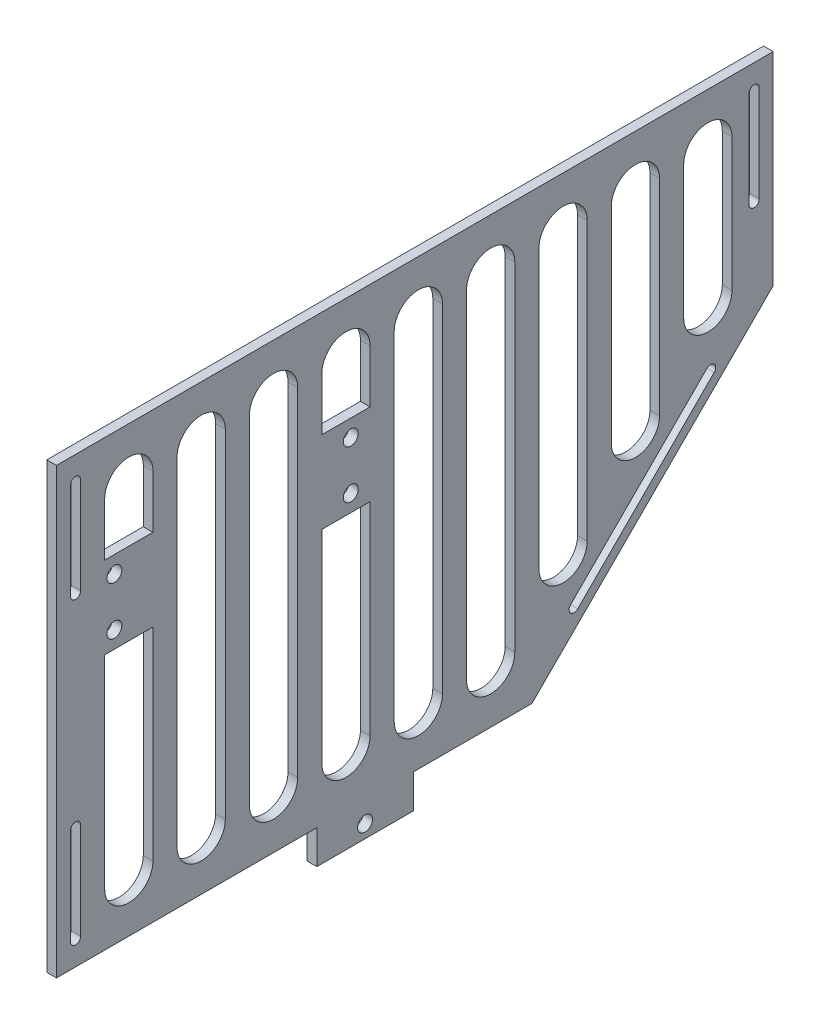
SolidWorks part; units mm, degrees
material "A-玻璃纤维"
ref_plane "前视基准面" through (0, 0, 0) normal (0, 0, 1) x (1, 0, 0)
ref_plane "上视基准面" through (0, 0, 0) normal (0, 1, 0) x (1, 0, 0)
ref_plane "右视基准面" through (0, 0, 0) normal (1, 0, 0) x (0, 0, -1)
sketch "草图2" plane through (0, 0, 0) normal (1, 0, 0) x (0, 0, -1)
  line L1 (-74.275, 46) -> (74.275, 46)
  line L2 (-74.275, 46) -> (-74.275, -46)
  line L3 (-74.275, -46) -> (74.275, -46)
  line L4 (74.275, 46) -> (74.275, -46)
  line L5 (0, -46) -> (0, 46) construction
  line L6 (-74.275, 0) -> (74.275, 0) construction
  point P0 (0, 0)
  dimension "D1" = 148.55
  dimension "D2" = 92
extrude "凸台-拉伸1" add sketch "草图2" along normal blind 2
sketch "草图3" plane through (2, 0, 0) normal (1, 0, 0) x (0, 0, -1)
  line L0 (24.275, -46) -> (74.275, 4)
  line L1 (-74.275, -46) -> (74.275, -46) construction
  line L2 (74.275, -46) -> (74.275, 46) construction
  dimension "D1" = 50
  dimension "D2" = 50
extrude "切除-拉伸1" cut sketch "草图3" against normal blind 2 and the other way through all flip side to cut
sketch "草图4" plane through (2, 0, 0) normal (1, 0, 0) x (0, 0, -1)
  line L0 (-70.315, -41) -> (-70.315, -21) construction
  line L1 (-71.365, -41) -> (-71.365, -21)
  line L2 (-69.265, -41) -> (-69.265, -21)
  line L3 (-74.275, -46) -> (24.275, -46) construction
  line L4 (-74.275, 46) -> (-74.275, -46) construction
  line L5 (-89.4732, 0) -> (86.2417, 0) construction
  line L6 (-70.315, 41) -> (-70.315, 21) construction
  line L7 (-71.365, 41) -> (-71.365, 21)
  line L8 (-69.265, 41) -> (-69.265, 21)
  line L9 (0, 54.2027) -> (0, -13.2498) construction
  line L10 (70.315, 41) -> (70.315, 21) construction
  line L11 (71.365, 41) -> (71.365, 21)
  line L12 (69.265, 41) -> (69.265, 21)
  arc A0 (-71.365, -41) -> (-69.265, -41) centre (-70.315, -41) ccw
  arc A1 (-69.265, -21) -> (-71.365, -21) centre (-70.315, -21) ccw
  arc A2 (-71.365, 41) -> (-69.265, 41) centre (-70.315, 41) cw
  arc A3 (-69.265, 21) -> (-71.365, 21) centre (-70.315, 21) cw
  arc A4 (71.365, 41) -> (69.265, 41) centre (70.315, 41) ccw
  arc A5 (69.265, 21) -> (71.365, 21) centre (70.315, 21) ccw
  point P2 (-70.315, -31)
  point P16 (-70.315, 31)
  point P25 (70.315, 31)
  dimension "D1" = 2.1
  dimension "D2" = 20
  dimension "D3" = 15
  dimension "D4" = 3.96
extrude "切除-拉伸2" cut sketch "草图4" against normal blind 2
sketch "草图5" plane through (2, 0, 0) normal (1, 0, 0) x (0, 0, -1)
  line L0 (-74.275, -46) -> (24.275, -46) construction
  line L1 (-20.315, -46) -> (-0.315, -46)
  line L2 (-20.315, -46) -> (-20.315, -53)
  line L3 (-20.315, -53) -> (-0.315, -53)
  line L4 (-0.315, -46) -> (-0.315, -53)
  line L5 (-74.275, 46) -> (-74.275, -46) construction
  line L6 (-10.315, -53) -> (-10.315, -50.25) construction
  circle A0 centre (-10.315, -50.25) radius 1.55
  dimension "D4" = 3.1
  dimension "D5" = 2.75
  dimension "D1" = 7
  dimension "D2" = 20
  dimension "D3" = 53.96
extrude "凸台-拉伸2" add sketch "草图5" against normal up to surface (2 mm away) up to face at (0, 31, 70.315)
sketch "草图6" plane through (2, 0, 0) normal (1, 0, 0) x (0, 0, -1)
  line L0 (-59.275, -35) -> (-59.275, 35) construction
  line L1 (-64.275, -35) -> (-64.275, 35)
  line L2 (-54.275, -35) -> (-54.275, 35)
  line L3 (15.725, -35) -> (15.725, 35) construction
  line L4 (-44.275, -35) -> (-44.275, 35) construction
  line L5 (-49.275, -35) -> (-49.275, 35)
  line L6 (-39.275, -35) -> (-39.275, 35)
  line L7 (-29.275, -35) -> (-29.275, 35) construction
  line L8 (-34.275, -35) -> (-34.275, 35)
  line L9 (-24.275, -35) -> (-24.275, 35)
  line L10 (-14.275, -35) -> (-14.275, 35) construction
  line L11 (-19.275, -35) -> (-19.275, 35)
  line L12 (-9.275, -35) -> (-9.275, 35)
  line L13 (0.725, -35) -> (0.725, 35) construction
  line L14 (-4.275, -35) -> (-4.275, 35)
  line L15 (5.725, -35) -> (5.725, 35)
  line L16 (-74.275, 46) -> (-74.275, -46) construction
  line L17 (-59.275, 0) -> (0, 0) construction
  line L18 (10.725, -35) -> (10.725, 35)
  line L19 (20.725, -35) -> (20.725, 35)
  line L20 (30.725, -22.5794) -> (30.725, 35) construction
  line L21 (25.725, -22.5794) -> (25.725, 35)
  line L22 (35.725, -22.5794) -> (35.725, 35)
  line L23 (45.725, -7.5794) -> (45.725, 35) construction
  line L24 (40.725, -7.5794) -> (40.725, 35)
  line L25 (50.725, -7.5794) -> (50.725, 35)
  line L26 (19.51, -33.7945) -> (60.8738, 7.5694) construction
  line L27 (24.275, -46) -> (74.275, 4) construction
  line L28 (60.725, 7.4206) -> (60.725, 35) construction
  line L29 (55.725, 7.4206) -> (55.725, 35)
  line L30 (65.725, 7.4206) -> (65.725, 35)
  arc A0 (-64.275, -35) -> (-54.275, -35) centre (-59.275, -35) ccw
  arc A1 (-54.275, 35) -> (-64.275, 35) centre (-59.275, 35) ccw
  arc A2 (-49.275, -35) -> (-39.275, -35) centre (-44.275, -35) ccw
  arc A3 (-39.275, 35) -> (-49.275, 35) centre (-44.275, 35) ccw
  arc A4 (-34.275, -35) -> (-24.275, -35) centre (-29.275, -35) ccw
  arc A5 (-24.275, 35) -> (-34.275, 35) centre (-29.275, 35) ccw
  arc A6 (-19.275, -35) -> (-9.275, -35) centre (-14.275, -35) ccw
  arc A7 (-9.275, 35) -> (-19.275, 35) centre (-14.275, 35) ccw
  arc A8 (-4.275, -35) -> (5.725, -35) centre (0.725, -35) ccw
  arc A9 (5.725, 35) -> (-4.275, 35) centre (0.725, 35) ccw
  arc A10 (10.725, -35) -> (20.725, -35) centre (15.725, -35) ccw
  arc A11 (20.725, 35) -> (10.725, 35) centre (15.725, 35) ccw
  arc A12 (25.725, -22.5794) -> (35.725, -22.5794) centre (30.725, -22.5794) ccw
  arc A13 (35.725, 35) -> (25.725, 35) centre (30.725, 35) ccw
  arc A14 (40.725, -7.5794) -> (50.725, -7.5794) centre (45.725, -7.5794) ccw
  arc A15 (50.725, 35) -> (40.725, 35) centre (45.725, 35) ccw
  arc A16 (55.725, 7.4206) -> (65.725, 7.4206) centre (60.725, 7.4206) ccw
  arc A17 (65.725, 35) -> (55.725, 35) centre (60.725, 35) ccw
  point P2 (-59.275, 0)
  point P10 (-44.275, 0)
  point P17 (-29.275, 0)
  point P24 (-14.275, 0)
  point P31 (0.725, 0)
  point P42 (15.725, 0)
  point P49 (30.725, 6.2103)
  point P56 (45.725, 13.7103)
  point P65 (60.725, 21.2103)
  dimension "D1" = 5
  dimension "D6" = 5
  dimension "D10" = 5
  dimension "D11" = 5
  dimension "D2" = 6
  dimension "D3" = 15
  dimension "D4" = 15
  dimension "D5" = 70
  dimension "D7" = 15
  dimension "D8" = 12
  dimension "D9" = 15
  dimension "D12" = 15
extrude "切除-拉伸3" cut sketch "草图6" against normal blind 2
sketch "草图7" plane through (2, 0, 0) normal (1, 0, 0) x (0, 0, -1)
  line L0 (-74.275, 46) -> (-74.275, -46) construction
  line L1 (-62.275, 20.5) -> (-13.275, 20.5) construction
  line L2 (-62.275, 20.5) -> (-62.275, 10.5) construction
  line L3 (-62.275, 10.5) -> (-13.275, 10.5) construction
  line L4 (-13.275, 20.5) -> (-13.275, 10.5) construction
  line L5 (-37.775, 10.5) -> (-37.775, 20.5) construction
  line L6 (-62.275, 15.5) -> (-13.275, 15.5) construction
  line L7 (74.275, 46) -> (-74.275, 46) construction
  circle A0 centre (-62.275, 10.5) radius 1.55
  circle A1 centre (-13.275, 10.5) radius 1.55
  circle A2 centre (-13.275, 20.5) radius 1.55
  circle A3 centre (-62.275, 20.5) radius 1.55
  point P0 (-37.775, 15.5)
  dimension "D3" = 3.1
  dimension "D5" = 35.5
  dimension "D1" = 10
  dimension "D2" = 49
  dimension "D4" = 12
sketch "草图8" plane through (2, 0, 0) normal (1, 0, 0) x (0, 0, -1)
  line L0 (-64.275, 35) -> (-64.275, -35) construction
  line L1 (-64.275, 7) -> (-54.275, 7)
  line L2 (-64.275, 7) -> (-64.275, 24)
  line L3 (-64.275, 24) -> (-54.275, 24)
  line L4 (-54.275, 7) -> (-54.275, 24)
  line L5 (-54.275, -35) -> (-54.275, 35) construction
  line L6 (-19.275, 35) -> (-19.275, -35) construction
  line L7 (-19.275, 7) -> (-9.275, 7)
  line L8 (-19.275, 7) -> (-19.275, 24)
  line L9 (-19.275, 24) -> (-9.275, 24)
  line L10 (-9.275, 7) -> (-9.275, 24)
  line L11 (-9.275, -35) -> (-9.275, 35) construction
  line L13 (74.275, 46) -> (-74.275, 46) construction
  dimension "D1" = 17
  dimension "D2" = 22
extrude "凸台-拉伸3" add sketch "草图8" against normal up to surface (2 mm away) up to face at (0, 0, 44.275)
extrude "切除-拉伸4" cut sketch "草图7" against normal blind 2
sketch "草图9" plane through (2, 0, 0) normal (1, 0, 0) x (0, 0, -1)
  line L0 (33.0115, -33.0208) -> (61.2958, -4.7365) construction
  line L1 (24.275, -46) -> (74.275, 4) construction
  line L2 (32.2691, -32.2784) -> (60.5534, -3.9941)
  line L3 (33.754, -33.7633) -> (62.0383, -5.479)
  line L4 (49.275, -21) -> (47.1537, -18.8787) construction
  arc A0 (32.2691, -32.2784) -> (33.754, -33.7633) centre (33.0115, -33.0208) ccw
  arc A1 (62.0383, -5.479) -> (60.5534, -3.9941) centre (61.2958, -4.7365) ccw
  point P4 (47.1537, -18.8787)
  point P10 (49.275, -21)
  dimension "D1" = 40
  dimension "D2" = 2.1
  dimension "D3" = 3
extrude "切除-拉伸5" cut sketch "草图9" against normal blind 2
